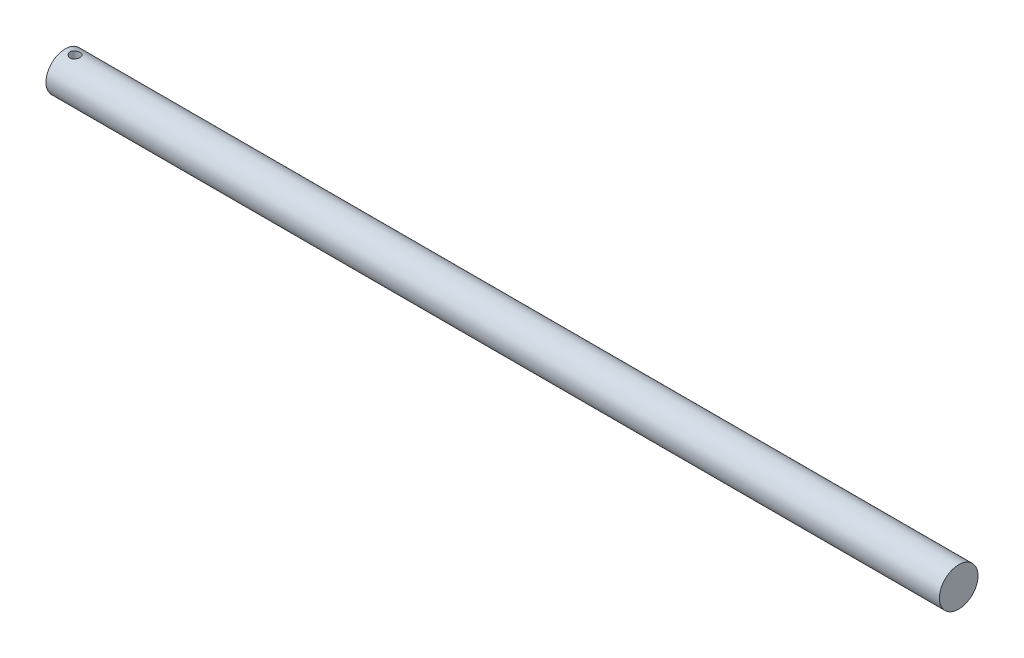
SolidWorks part; units mm, degrees
ref_plane "Front Plane" through (0, 0, 0) normal (0, 0, 1) x (1, 0, 0)
ref_plane "Top Plane" through (0, 0, 0) normal (0, 1, 0) x (1, 0, 0)
ref_plane "Right Plane" through (0, 0, 0) normal (1, 0, 0) x (0, 0, -1)
sketch "Sketch1" plane through (0, 0, 0) normal (1, 0, 0) x (0, 0, -1)
  circle A0 centre (0, 0) radius 4.85
  dimension "D1" = 9.7
extrude "Boss-Extrude1" add sketch "Sketch1" along normal blind 224.6937
sketch "Sketch2" plane through (0, 0, 0) normal (0, 1, 0) x (1, 0, 0)
  circle A0 centre (2.5, 0) radius 1.25
  dimension "D1" = 2.5
  dimension "D2" = 2.5
extrude "Cut-Extrude1" cut sketch "Sketch2" against normal through all both and the other way through all
scale "Scale1" scale about centroid uniform scaling yes scale factor 1.5
